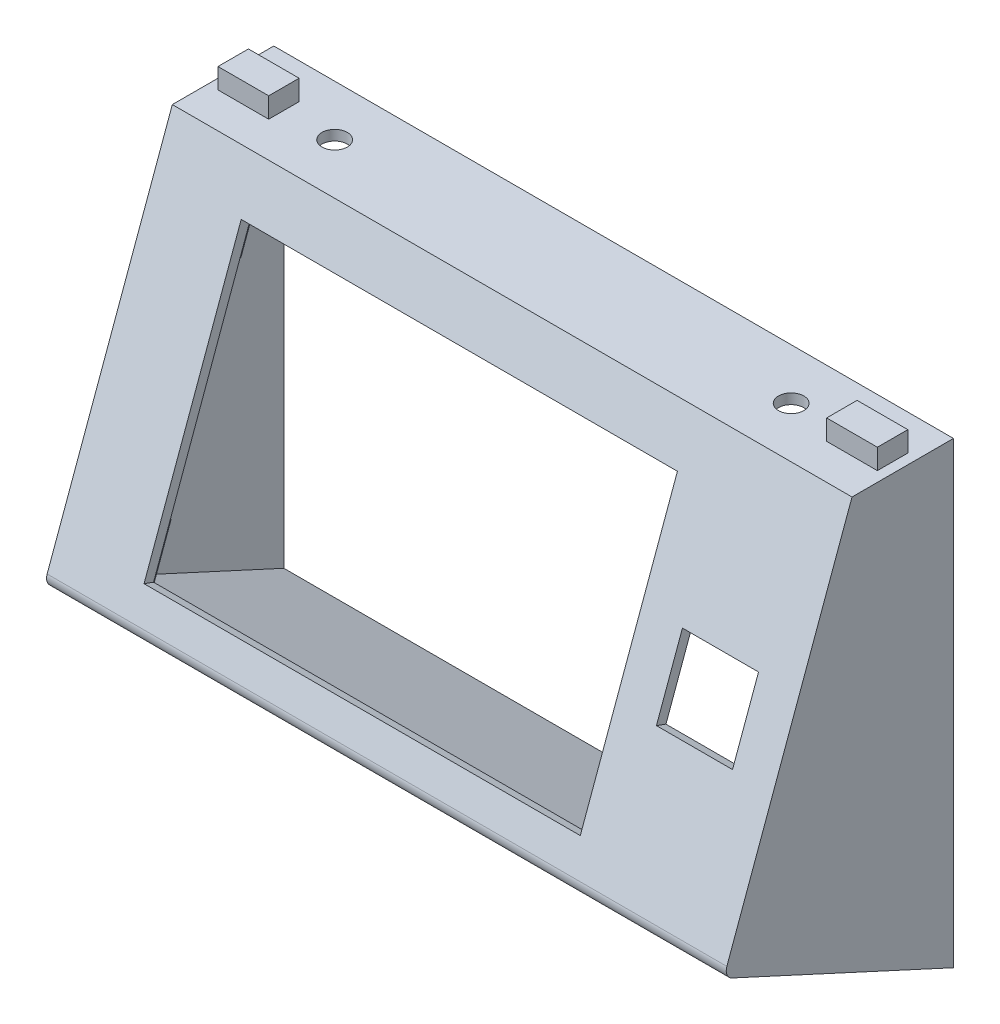
SolidWorks part; units mm, degrees
ref_plane "Спереди" through (0, 0, 0) normal (0, 0, 1) x (1, 0, 0)
ref_plane "Сверху" through (0, 0, 0) normal (0, 1, 0) x (1, 0, 0)
ref_plane "Справа" through (0, 0, 0) normal (1, 0, 0) x (0, 0, -1)
sketch "Эскиз1" plane through (0, 0, 0) normal (0, 1, 0) x (1, 0, 0)
  line L1 (0, 0) -> (130, 0)
  line L2 (0, 0) -> (0, 20)
  line L3 (0, 20) -> (130, 20)
  line L4 (130, 0) -> (130, 20)
  dimension "D1" = 20
  dimension "D2" = 130
extrude "Бобышка-Вытянуть1" add sketch "Эскиз1" along normal blind 2
sketch "Эскиз2" plane through (0, 2, 0) normal (0, 1, 0) x (1, 0, 0)
  line L0 (0, 20) -> (0, 0) construction
  line L1 (0, 13) -> (10, 13)
  line L2 (0, 13) -> (0, 7)
  line L3 (0, 7) -> (10, 7)
  line L4 (10, 13) -> (10, 7)
  line L5 (130, 0) -> (130, 20) construction
  line L6 (130, 7) -> (120, 7)
  line L7 (130, 7) -> (130, 13)
  line L8 (130, 13) -> (120, 13)
  line L9 (120, 7) -> (120, 13)
  point P12 (0, 10)
  point P13 (0, 10)
  point P14 (10, 10)
  dimension "D1" = 6
  dimension "D2" = 10
  dimension "D3" = 10
extrude "Бобышка-Вытянуть2" add sketch "Эскиз2" along normal blind 4
sketch "Эскиз3" plane through (0, 2, 0) normal (0, 1, 0) x (1, 0, 0)
  line L0 (130, 7) -> (130, 13) construction
  line L1 (10, 7) -> (10, 13) construction
  circle A0 centre (20, 10) radius 2.5
  circle A1 centre (110, 10) radius 2.5
  point P7 (130, 10)
  point P11 (10, 10)
  dimension "D1" = 5
  dimension "D2" = 10
  dimension "D3" = 10
extrude "Вырез-Вытянуть1" cut sketch "Эскиз3" against normal blind 4
ref_plane "Плоскость1" through (0, 0.234, 0.6428) normal (0, -0.342, -0.9397) x (1, 0, 0)
sketch "Эскиз4" plane through (0, 0.234, 0.6428) normal (0, -0.342, -0.9397) x (1, 0, 0)
  line L1 (0, -1.8794) -> (130, -1.8794)
  line L2 (0, -1.8794) -> (0, 72.1206)
  line L3 (0, 72.1206) -> (130, 72.1206)
  line L4 (130, -1.8794) -> (130, 72.1206)
  line L5 (15, 8.1206) -> (101, 8.1206)
  line L6 (15, 8.1206) -> (15, 64.1206)
  line L7 (15, 64.1206) -> (101, 64.1206)
  line L8 (101, 8.1206) -> (101, 64.1206)
  line L9 (109, 43.6206) -> (124, 43.6206)
  line L10 (109, 43.6206) -> (109, 28.6206)
  line L11 (109, 28.6206) -> (124, 28.6206)
  line L12 (124, 43.6206) -> (124, 28.6206)
  point P9 (109, 36.1206)
  point P15 (101, 36.1206)
  dimension "D1" = 56
  dimension "D2" = 86
  dimension "D3" = 74
  dimension "D4" = 15
  dimension "D5" = 10
  dimension "D6" = 15
  dimension "D7" = 15
  dimension "D8" = 8
extrude "Бобышка-Вытянуть3" add sketch "Эскиз4" along normal blind 2
sketch "Эскиз5" plane through (130, 0, 0) normal (1, 0, 0) x (0, 0, -1)
  line L0 (7, 2) -> (13, 2)
  line L1 (20, 0) -> (20, -88.3758)
  line L2 (20, -88.3758) -> (-23.4863, -68.3758)
  line L10 (7, 2) -> (0, 2)
  line L11 (0, 2) -> (-25.3095, -67.5373)
  line L12 (-25.3095, -67.5373) -> (-23.4301, -68.2213)
  line L13 (-23.4301, -68.2213) -> (1.4004, 0)
  line L14 (1.4004, 0) -> (20, 0)
  line L15 (20, 0) -> (20, 2)
  line L16 (20, 2) -> (13, 2)
  line L17 (13, 2) -> (13, 6)
  line L18 (13, 6) -> (7, 6)
  line L19 (7, 6) -> (7, 2)
  line L20 (7, 2) -> (0, 2)
  line L21 (0, 2) -> (-25.3095, -67.5373)
  line L22 (-25.3095, -67.5373) -> (-23.4863, -68.3758)
  line L23 (-23.4863, -68.3758) -> (1.4004, 0)
  line L24 (1.4004, 0) -> (20, 0)
  line L25 (20, 0) -> (20, 2)
  line L26 (20, 2) -> (13, 2)
  line L27 (13, 2) -> (13, 6)
  line L28 (13, 6) -> (7, 6)
  line L29 (7, 6) -> (7, 2)
  line M11 (7, 2) -> (0, 2)
  line M12 (0, 2) -> (-25.3095, -67.5373)
  line M13 (-25.3095, -67.5373) -> (-23.4301, -68.2213)
  line M14 (-23.4301, -68.2213) -> (1.4004, 0)
  line M15 (1.4004, 0) -> (20, 0)
  line M16 (20, 0) -> (20, 2)
  line M17 (20, 2) -> (13, 2)
  dimension "D2" = 20
  dimension "D1" = 0
extrude "Бобышка-Вытянуть4" add sketch "Эскиз5" along normal blind 2 contours L2 L1 M15 M14 | L0 M11 M12 M13 M14 M15 M16 M17 | L22 L23 M13
sketch "Эскиз7" plane through (0, 0, 0) normal (-1, 0, 0) x (0, 0, 1)
  line L0 (-13, 2) -> (-7, 2)
  line L1 (-20, 0) -> (-20, -88.3758)
  line L2 (-20, -88.3758) -> (23.4863, -68.3758)
  line L10 (-20, 0) -> (-1.4004, 0)
  line L11 (-1.4004, 0) -> (23.4301, -68.2213)
  line L12 (23.4301, -68.2213) -> (25.3095, -67.5373)
  line L13 (25.3095, -67.5373) -> (0, 2)
  line L14 (0, 2) -> (-7, 2)
  line L15 (-7, 2) -> (-7, 6)
  line L16 (-7, 6) -> (-13, 6)
  line L17 (-13, 6) -> (-13, 2)
  line L18 (-13, 2) -> (-20, 2)
  line L19 (-20, 2) -> (-20, 0)
  line L20 (-20, 0) -> (-1.4004, 0)
  line L21 (-1.4004, 0) -> (23.4863, -68.3758)
  line L22 (23.4863, -68.3758) -> (25.3095, -67.5373)
  line L23 (25.3095, -67.5373) -> (0, 2)
  line L24 (0, 2) -> (-7, 2)
  line L25 (-7, 2) -> (-7, 6)
  line L26 (-7, 6) -> (-13, 6)
  line L27 (-13, 6) -> (-13, 2)
  line L28 (-13, 2) -> (-20, 2)
  line L29 (-20, 2) -> (-20, 0)
  line M12 (-20, 0) -> (-1.4004, 0)
  line M13 (-1.4004, 0) -> (23.4301, -68.2213)
  line M14 (23.4301, -68.2213) -> (25.3095, -67.5373)
  line M15 (25.3095, -67.5373) -> (0, 2)
  line M16 (0, 2) -> (-7, 2)
  line M20 (-13, 2) -> (-20, 2)
  line M21 (-20, 2) -> (-20, 0)
  dimension "D1" = 0
extrude "Бобышка-Вытянуть5" add sketch "Эскиз7" along normal blind 2 contours L0 M20 M21 M12 M13 M14 M15 M16 | L1 L2 M13 M12 | L21 L22 M14
sketch "Эскиз8" plane through (130, 0, 0) normal (-1, 0, 0) x (0, 0, 1)
  line L0 (-20, -86.1744) -> (22.8, -66.49)
  line L1 (-20, 0) -> (-20, -88.3758) construction
  line L2 (-1.4004, 0) -> (23.4301, -68.2213) construction
  line L3 (22.8, -66.49) -> (25.3095, -67.5373)
  line L4 (25.3095, -67.5373) -> (-20, -88.3758)
  line L5 (-20, -88.3758) -> (-20, -86.1744)
  dimension "D1" = 2
extrude "Бобышка-Вытянуть6" add sketch "Эскиз8" along normal up to vertex (130 mm away)
sketch "Эскиз9" plane through (0, -0.4501, -1.2366) normal (0, -0.342, -0.9397) x (-1, 0, 0)
  line L0 (-130, 0.479) -> (-130, -70.2782) construction
  line L1 (-130, -16.021) -> (-120, -16.021)
  line L2 (-130, -16.021) -> (-130, 1.979)
  line L3 (-130, 1.979) -> (-120, 1.979)
  line L4 (-120, -16.021) -> (-120, 1.979)
  line L5 (0, -70.2782) -> (0, 0.479) construction
  line L6 (0, -16.021) -> (-12, -16.021)
  line L7 (0, -16.021) -> (0, 1.979)
  line L8 (0, 1.979) -> (-12, 1.979)
  line L9 (-12, -16.021) -> (-12, 1.979)
  line L10 (-130, 0.479) -> (0, 0.479) construction
  line L11 (0, -56.2782) -> (-12, -56.2782)
  line L12 (0, -56.2782) -> (0, -71.2782)
  line L13 (0, -71.2782) -> (-12, -71.2782)
  line L14 (-12, -56.2782) -> (-12, -71.2782)
  line L15 (-130, -56.2782) -> (-120, -56.2782)
  line L16 (-130, -56.2782) -> (-130, -71.2782)
  line L17 (-130, -71.2782) -> (-120, -71.2782)
  line L18 (-120, -56.2782) -> (-120, -71.2782)
  line L19 (0, -70.2782) -> (-130, -70.2782) construction
  dimension "D1" = 12
  dimension "D2" = 10
  dimension "D3" = 18
  dimension "D4" = 15
  dimension "D5" = 1.5
  dimension "D6" = 1
extrude "Бобышка-Вытянуть7" add sketch "Эскиз9" along normal blind 4
sketch "Эскиз10" plane through (0, -1.8182, -4.9954) normal (0, -0.342, -0.9397) x (-1, 0, 0)
  line L0 (-15, -64.1206) -> (-15, -8.1206) construction
  line L2 (-15, -8.1206) -> (-101, -8.1206) construction
  circle A0 centre (-7.5, -8.6206) radius 2.25
  circle A1 centre (-124.5, -8.6206) radius 2.25
  circle A2 centre (-7.5, -65.6206) radius 2.25
  circle A3 centre (-124.5, -65.6206) radius 2.25
  dimension "D1" = 4.5
  dimension "D2" = 117
  dimension "D3" = 57
  dimension "D4" = 7.5
  dimension "D5" = 0.5
extrude "Вырез-Вытянуть2" cut sketch "Эскиз10" against normal blind 5 contours A1 | A2 | A3 | A0
sketch "Эскиз11" plane through (120, 0, 0) normal (-1, 0, 0) x (0, 0, 1)
  line L0 (0.7372, -5.8731) -> (2.6183, -11.0414)
  line L1 (4.2429, -15.5049) -> (-1.4004, 0) construction
  line L2 (2.6183, -11.0414) -> (0.645, -11.7596)
  line L3 (0.645, -11.7596) -> (-1.2361, -6.5913)
  line L4 (-1.2361, -6.5913) -> (0.7372, -5.8731)
  line L13 (0.4841, -16.873) -> (4.2429, -15.5049) construction
  line L14 (20.147, -59.201) -> (18.1736, -59.9192)
  line L15 (18.1736, -59.9192) -> (20.0547, -65.0876)
  line L16 (20.0547, -65.0876) -> (22.0281, -64.3693)
  line L17 (22.8, -66.49) -> (18.0117, -53.3343) construction
  line L18 (22.0281, -64.3693) -> (20.147, -59.201)
  line L19 (19.1536, -68.167) -> (22.8, -66.49) construction
  point P0 (-0.2956, -9.1755)
  point P15 (21.0875, -61.7852)
  dimension "D1" = 2.1
  dimension "D2" = 5.5
  dimension "D3" = 7.5
  dimension "D4" = 4.99
extrude "Вырез-Вытянуть3" cut sketch "Эскиз11" against normal blind 9 and the other way blind 118
fillet "Скругление1" radius 2 1 edges at (66, -66.49, 22.8)
fillet "Скругление2" radius 2 1 edges at (65, -67.5373, 25.3095)
